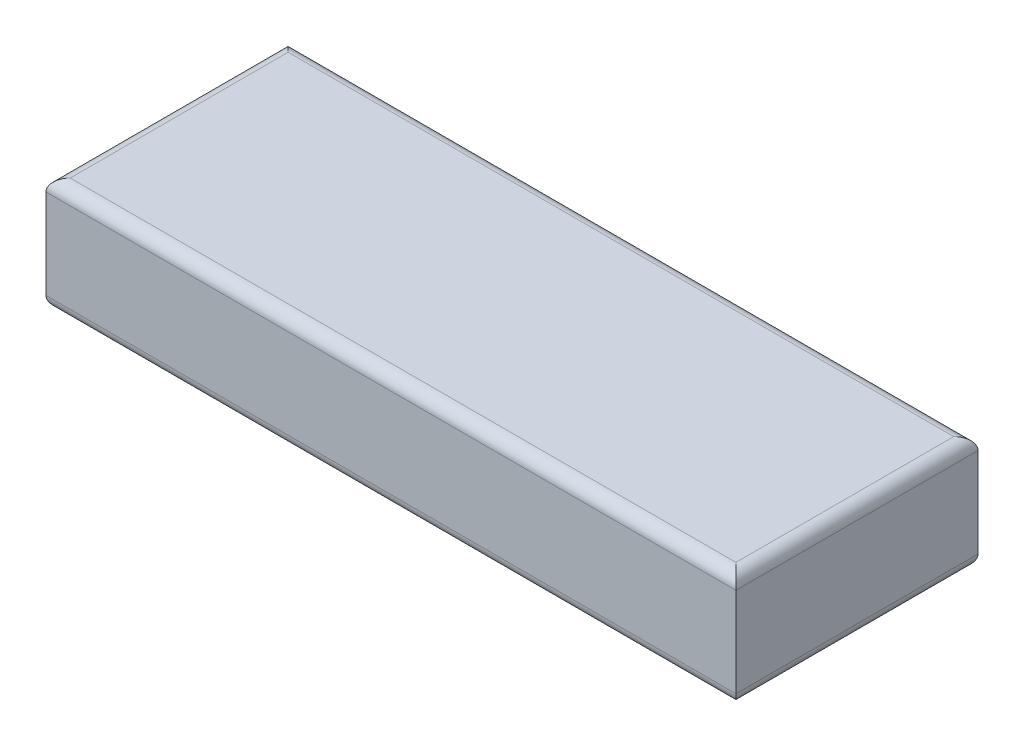
SolidWorks part; units mm, degrees
ref_plane "Front Plane" through (0, 0, 0) normal (0, 0, 1) x (1, 0, 0)
ref_plane "Top Plane" through (0, 0, 0) normal (0, 1, 0) x (1, 0, 0)
ref_plane "Right Plane" through (0, 0, 0) normal (1, 0, 0) x (0, 0, -1)
sketch "Sketch1" plane through (0, 0, 0) normal (0, 1, 0) x (1, 0, 0)
  line L1 (-14.478, 5.08) -> (14.478, 5.08)
  line L2 (-14.478, 5.08) -> (-14.478, -5.08)
  line L3 (-14.478, -5.08) -> (14.478, -5.08)
  line L4 (14.478, 5.08) -> (14.478, -5.08)
  line L5 (-14.478, 5.08) -> (14.478, -5.08) construction
  line L6 (-14.478, -5.08) -> (14.478, 5.08) construction
  point P0 (0, 0)
  dimension "D1" = 28.956
  dimension "D2" = 10.16
extrude "Boss-Extrude1" add sketch "Sketch1" along normal blind 4.7753
fillet "Fillet1" radius 0.508 8 edges at (0, 4.7753, 5.08) (-14.478, 4.7753, 0) (0, 4.7753, -5.08) (14.478, 4.7753, 0) (0, 0, -5.08) (-14.478, 0, 0) (0, 0, 5.08) (14.478, 0, 0)
